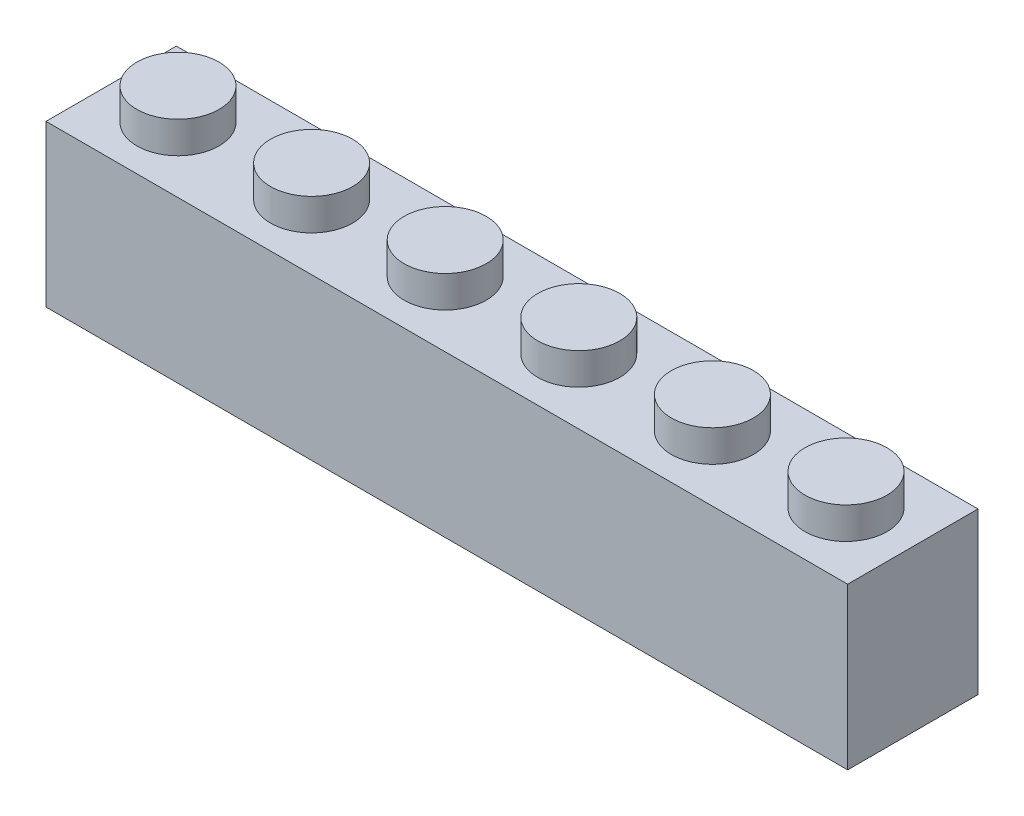
SolidWorks part; units mm, degrees
ref_plane "Front Plane" through (0, 0, 0) normal (0, 0, 1) x (1, 0, 0)
ref_plane "Top Plane" through (0, 0, 0) normal (0, 1, 0) x (1, 0, 0)
ref_plane "Right Plane" through (0, 0, 0) normal (1, 0, 0) x (0, 0, -1)
sketch "Sketch1" plane through (0, 0, 0) normal (0, 0, 1) x (1, 0, 0)
  line L1 (-23.925, 4.8) -> (23.925, 4.8)
  line L2 (-23.925, 4.8) -> (-23.925, -4.8)
  line L3 (-23.925, -4.8) -> (23.925, -4.8)
  line L4 (23.925, 4.8) -> (23.925, -4.8)
  line L5 (-23.925, 4.8) -> (23.925, -4.8) construction
  line L6 (-23.925, -4.8) -> (23.925, 4.8) construction
  point P0 (0, 0)
  dimension "D1" = 9.6
  dimension "D2" = 47.85
extrude "Boss-Extrude1" add sketch "Sketch1" against normal blind 7.78
sketch "Sketch2" plane through (0, 4.8, 0) normal (0, 1, 0) x (1, 0, 0)
  line L1 (-23.925, 7.78) -> (-23.925, 0) construction
  line L2 (23.925, 7.78) -> (-23.925, 7.78) construction
  circle A0 centre (-19.9375, 3.89) radius 2.45
  circle A1 centre (-11.9625, 3.89) radius 2.45
  circle A2 centre (-3.9875, 3.89) radius 2.45
  circle A3 centre (3.9875, 3.89) radius 2.45
  circle A4 centre (11.9625, 3.89) radius 2.45
  circle A5 centre (19.9375, 3.89) radius 2.45
  point P6 (-23.925, 3.89)
  dimension "D1" = 3.9875
  dimension "D3" = 4.9
  dimension "D5" = 7.975
  dimension "D2" = 3.89
  dimension "D4" = 6
extrude "Boss-Extrude2" add sketch "Sketch2" along normal blind 1.89
shell "Shell1" thickness 1.5
sketch "Sketch3" plane through (0, 3.3, 0) normal (0, -1, 0) x (1, 0, 0)
  line L1 (22.425, -1.5) -> (-22.425, -1.5) construction
  line L4 (-23.925, -7.78) -> (-23.925, 0) construction
  circle A0 centre (-15.95, -3.89) radius 1.48
  circle A1 centre (-7.975, -3.89) radius 1.48
  circle A2 centre (0, -3.89) radius 1.48
  circle A3 centre (7.975, -3.89) radius 1.48
  circle A4 centre (15.95, -3.89) radius 1.48
  dimension "D1" = 2.39
  dimension "D2" = 7.975
  dimension "D3" = 2.96
  dimension "D5" = 7.975
  dimension "D4" = 5
extrude "Boss-Extrude3" add sketch "Sketch3" along normal offset from surface (7.9 mm away) 0.2 up to face at (0, -4.8, -3.89)
